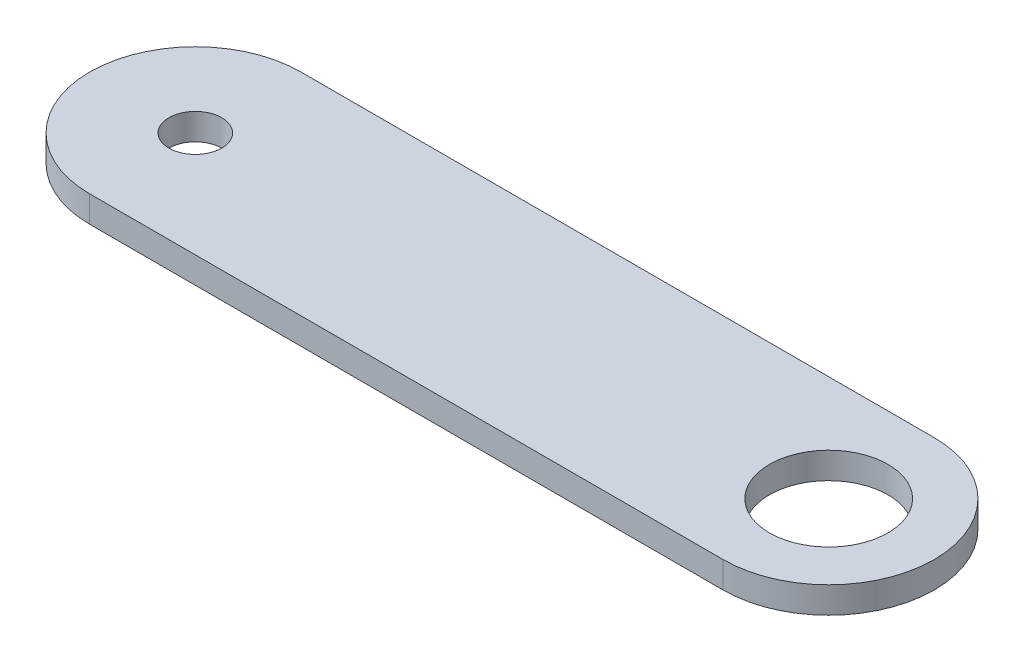
SolidWorks part; units mm, degrees
material "6061-T4 (SS)"
ref_plane "Front Plane" through (0, 0, 0) normal (0, 0, 1) x (1, 0, 0)
ref_plane "Top Plane" through (0, 0, 0) normal (0, 1, 0) x (1, 0, 0)
ref_plane "Right Plane" through (0, 0, 0) normal (1, 0, 0) x (0, 0, -1)
sketch "Sketch1" plane through (0, 0, 0) normal (0, 1, 0) x (1, 0, 0)
  line L0 (19.05, 0) -> (-19.05, 0) construction
  line L1 (19.05, -6.35) -> (-19.05, -6.35)
  line L2 (19.05, 6.35) -> (-19.05, 6.35)
  arc A0 (19.05, -6.35) -> (19.05, 6.35) centre (19.05, 0) ccw
  arc A1 (-19.05, 6.35) -> (-19.05, -6.35) centre (-19.05, 0) ccw
  circle A2 centre (-19.05, 0) radius 1.5875
  circle A3 centre (19.05, 0) radius 3.5687
  point P2 (0, 0)
  point P13 (-25.4, 0)
  point P15 (25.4, 0)
  dimension "D1" = 3.175
  dimension "D3" = 6.35
  dimension "D6" = 7.1374
  dimension "D2" = 6.35
  dimension "D4" = 50.8
  dimension "D5" = 12.7
extrude "Boss-Extrude1" add sketch "Sketch1" along normal blind 1.5875
